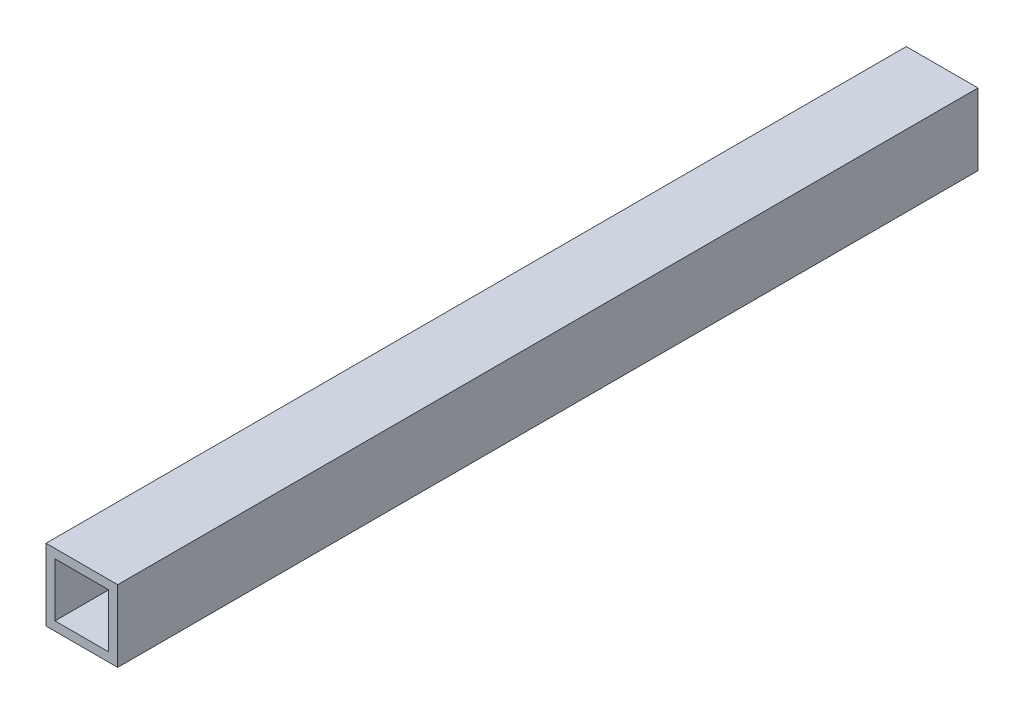
SolidWorks part; units mm, degrees
ref_plane "Front Plane" through (0, 0, 0) normal (0, 0, 1) x (1, 0, 0)
ref_plane "Top Plane" through (0, 0, 0) normal (0, 1, 0) x (1, 0, 0)
ref_plane "Right Plane" through (0, 0, 0) normal (1, 0, 0) x (0, 0, -1)
sketch "Sketch2" plane through (0, 0, 0) normal (0, 0, 1) x (1, 0, 0)
  line L1 (-25.4, -25.4) -> (25.4, -25.4)
  line L2 (-25.4, -25.4) -> (-25.4, 25.4)
  line L3 (-25.4, 25.4) -> (25.4, 25.4)
  line L4 (25.4, -25.4) -> (25.4, 25.4)
  line L5 (-25.4, -25.4) -> (25.4, 25.4) construction
  line L6 (-25.4, 25.4) -> (25.4, -25.4) construction
  line L7 (-19.05, -19.05) -> (19.05, -19.05)
  line L8 (-19.05, -19.05) -> (-19.05, 19.05)
  line L9 (-19.05, 19.05) -> (19.05, 19.05)
  line L10 (19.05, -19.05) -> (19.05, 19.05)
  line L11 (-19.05, -19.05) -> (19.05, 19.05) construction
  line L12 (-19.05, 19.05) -> (19.05, -19.05) construction
  point P1 (0, 0)
  point P6 (0, 0)
  dimension "D1" = 50.8
  dimension "D2" = 50.8
  dimension "D3" = 6.35
  dimension "D4" = 6.35
extrude "Boss-Extrude2" add sketch "Sketch2" along normal blind 609.6
